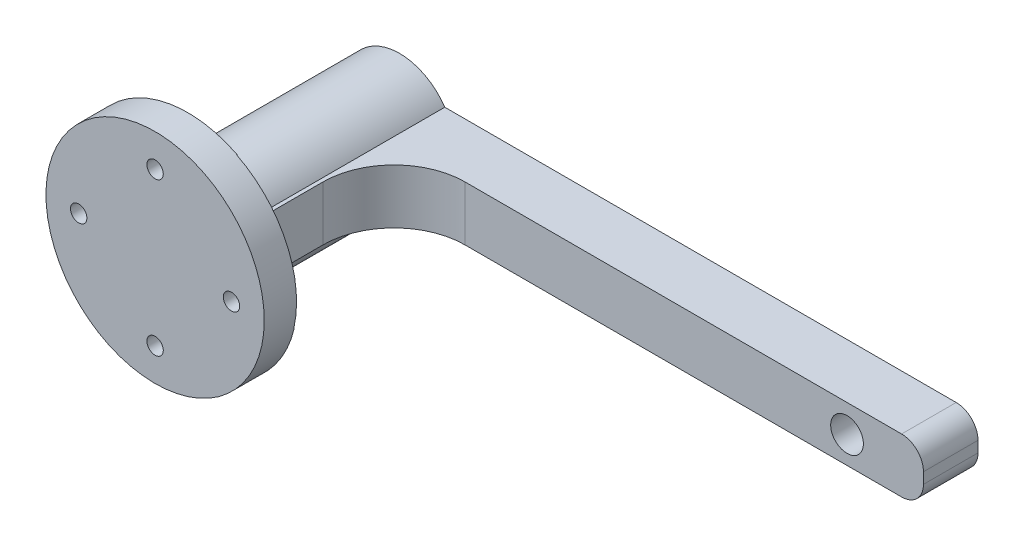
SolidWorks part; units mm, degrees
ref_plane "前视基准面" through (0, 0, 0) normal (0, 0, 1) x (1, 0, 0)
ref_plane "上视基准面" through (0, 0, 0) normal (0, 1, 0) x (1, 0, 0)
ref_plane "右视基准面" through (0, 0, 0) normal (1, 0, 0) x (0, 0, -1)
sketch "草图1" plane through (0, 0, 0) normal (0, 0, 1) x (1, 0, 0)
  circle A0 centre (0, 0) radius 10
  dimension "D1" = 20
extrude "凸台-拉伸1" add sketch "草图1" along normal blind 3
sketch "草图2" plane through (0, 0, 0) normal (0, 0, -1) x (-1, 0, 0)
  circle A0 centre (0, 7) radius 0.75
  circle A1 centre (7, 0) radius 0.75
  circle A2 centre (0, -7) radius 0.75
  circle A3 centre (-7, 0) radius 0.75
  point P12 (-0.725, 0.725)
  point P13 (0, 0)
  dimension "D1" = 1.5
  dimension "D2" = 7
  dimension "D3" = 4
extrude "切除-拉伸1" cut sketch "草图2" against normal through all
sketch "草图3" plane through (0, 0, 0) normal (0, 0, -1) x (-1, 0, 0)
  circle A0 centre (0, 0) radius 5
extrude "凸台-拉伸2" add sketch "草图3" along normal blind 19.4
sketch "草图6" plane through (0, 0, 0) normal (1, 0, 0) x (0, 0, -1)
  line L0 (0, -10) -> (0, 10) construction
  line L1 (0, 2.7988) -> (19.4, 2.7988)
  line L2 (0, 2.7988) -> (0, -2.2012)
  line L3 (0, -2.2012) -> (19.4, -2.2012)
  line L4 (19.4, 2.7988) -> (19.4, -2.2012)
  line L5 (19.4, -5) -> (19.4, 5) construction
  dimension "D1" = 5
extrude "凸台-拉伸4" add sketch "草图6" along normal blind 53
sketch "草图7" plane through (0, -2.2012, 0) normal (0, -1, 0) x (-1, 0, 0)
  line L5 (-4.4894, 0) -> (-4.4894, 19.4) construction
  line L6 (-4.4894, -0.0388) -> (-53, -0.0388)
  line L7 (-4.4894, -0.0388) -> (-4.4894, 7.9)
  line L8 (-10.9894, 14.4) -> (-53, 14.4)
  line L9 (-53, -0.0388) -> (-53, 14.4)
  line L10 (-53, 0) -> (-53, 19.4) construction
  arc A0 (-4.4894, 7.9) -> (-10.9894, 14.4) centre (-10.9894, 7.9) ccw
  dimension "D2" = 6.5
  dimension "D1" = 5
extrude "切除-拉伸2" cut sketch "草图7" against normal through all
sketch "草图8" plane through (0, 0, -19.4) normal (0, 0, -1) x (-1, 0, 0)
  line L0 (-53, -2.2012) -> (-53, 2.7988) construction
  line L1 (-53, 0.2988) -> (0.475, 0.0108) construction
  circle A0 centre (-46, 0.2611) radius 1.5
  dimension "D1" = 3
  dimension "D2" = 7
extrude "切除-拉伸3" cut sketch "草图8" against normal through all
fillet "圆角1" radius 2 2 edges at (53, 2.7988, -16.9) (53, -2.2012, -16.9)
